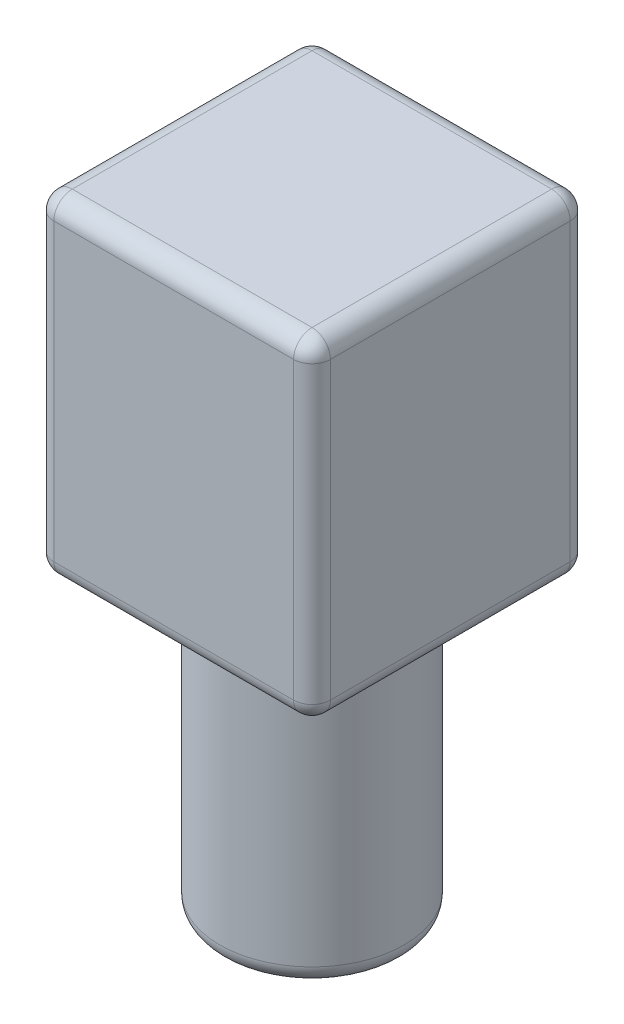
SolidWorks part; units mm, degrees
ref_plane "Front Plane" through (0, 0, 0) normal (0, 0, 1) x (1, 0, 0)
ref_plane "Top Plane" through (0, 0, 0) normal (0, 1, 0) x (1, 0, 0)
ref_plane "Right Plane" through (0, 0, 0) normal (1, 0, 0) x (0, 0, -1)
sketch "Sketch1" plane through (0, 0, 0) normal (0, 1, 0) x (1, 0, 0)
  circle A0 centre (0, 0) radius 10
extrude "Boss-Extrude1" add sketch "Sketch1" along normal blind 32 contours A0
sketch "Sketch2" plane through (0, 32, 0) normal (0, 1, 0) x (1, 0, 0)
  line L5 (-15, -15) -> (15, -15)
  line L6 (-15, -15) -> (-15, 15)
  line L7 (-15, 15) -> (15, 15)
  line L8 (15, -15) -> (15, 15)
  line L9 (-15, -15) -> (15, 15) construction
  line L10 (-15, 15) -> (15, -15) construction
  point P0 (0, 0)
extrude "Boss-Extrude2" add sketch "Sketch2" along normal blind 36 contours L7 L8 L5 L6
fillet "Fillet1" radius 2 13 edges at (-15, 32, 0) (0, 32, -15) (15, 32, 0) (0, 32, 15) (-15, 68, 0) (0, 68, -15) (15, 68, 0) (0, 68, 15) (-15, 50, -15) (15, 50, -15) (15, 50, 15) (-15, 50, 15) (0, 0, 10)
